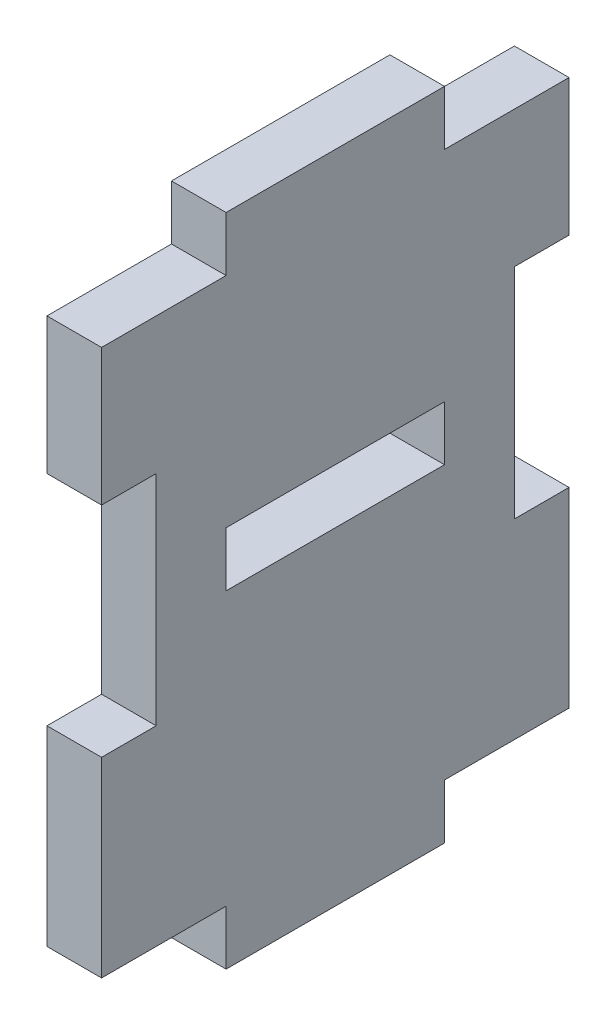
SolidWorks part; units mm, degrees
ref_plane "Front Plane" through (0, 0, 0) normal (0, 0, 1) x (1, 0, 0)
ref_plane "Top Plane" through (0, 0, 0) normal (0, 1, 0) x (1, 0, 0)
ref_plane "Right Plane" through (0, 0, 0) normal (1, 0, 0) x (0, 0, -1)
sketch "Sketch1" plane through (0, 0, 0) normal (1, 0, 0) x (0, 0, -1)
  line L0 (14.478, 0) -> (14.478, 6.35)
  line L1 (14.478, 0) -> (39.878, 0)
  line L2 (39.878, 0) -> (39.878, 6.35)
  line L3 (39.878, 6.35) -> (54.356, 6.35)
  line L4 (54.356, 6.35) -> (54.356, 28.575)
  line L5 (27.178, 6.35) -> (27.178, 69.85) construction
  line L7 (14.478, 44.45) -> (39.878, 44.45)
  line L8 (14.478, 69.85) -> (14.478, 76.2)
  line L9 (54.356, 69.85) -> (39.878, 69.85)
  line L10 (0, 69.85) -> (0, 53.975)
  line L11 (0, 6.35) -> (14.478, 6.35)
  line L12 (0, 6.35) -> (0, 0) construction
  line L13 (0, 0) -> (14.478, 0) construction
  line L14 (14.478, 76.2) -> (39.878, 76.2)
  line L15 (14.478, 6.35) -> (39.878, 6.35) construction
  line L16 (39.878, 76.2) -> (39.878, 69.85)
  line L17 (14.478, 69.85) -> (0, 69.85)
  line L18 (14.478, 69.85) -> (39.878, 69.85) construction
  line L19 (14.478, 44.45) -> (14.478, 38.1)
  line L20 (14.478, 38.1) -> (39.878, 38.1)
  line L21 (39.878, 44.45) -> (39.878, 38.1)
  line L34 (54.356, 53.975) -> (48.006, 53.975)
  line L35 (48.006, 53.975) -> (48.006, 28.575)
  line L36 (48.006, 28.575) -> (54.356, 28.575)
  line L37 (54.356, 53.975) -> (54.356, 69.85)
  line L45 (0, 53.975) -> (6.35, 53.975)
  line L46 (6.35, 53.975) -> (6.35, 28.575)
  line L47 (6.35, 28.575) -> (0, 28.575)
  line L49 (0, 28.575) -> (0, 6.35)
  point P15 (27.178, 44.45)
  dimension "D1" = 25.4
  dimension "D2" = 6.35
  dimension "D3" = 54.356
  dimension "D4" = 6.35
  dimension "D5" = 63.5
  dimension "D6" = 6.35
  dimension "D7" = 6.35
  dimension "D8" = 25.4
  dimension "D9" = 38.1
  dimension "D14" = 47.625
  dimension "D15" = 25.4
extrude "Extrude1" add sketch "Sketch1" along normal blind 6.35
